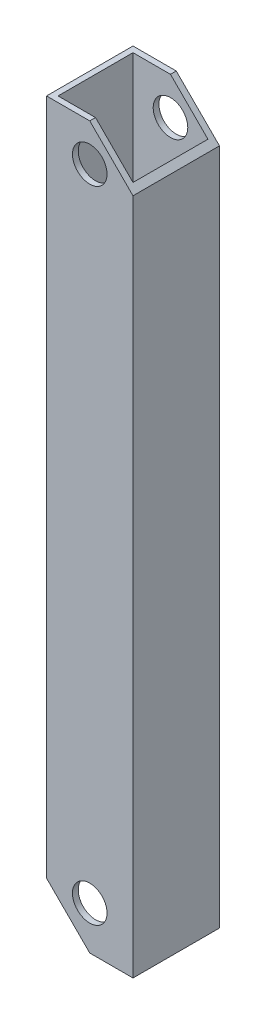
SolidWorks part; units mm, degrees
ref_plane "Front Plane" through (0, 0, 0) normal (0, 0, 1) x (1, 0, 0)
ref_plane "Top Plane" through (0, 0, 0) normal (0, 1, 0) x (1, 0, 0)
ref_plane "Right Plane" through (0, 0, 0) normal (1, 0, 0) x (0, 0, -1)
sketch "Эскиз1" plane through (0, 0, 0) normal (0, 1, 0) x (1, 0, 0)
  line L1 (0, 0) -> (30, 0)
  line L2 (0, 0) -> (0, 30)
  line L3 (0, 30) -> (30, 30)
  line L4 (30, 0) -> (30, 30)
  dimension "D1" = 30
  dimension "D2" = 30
extrude "Бобышка-Вытянуть1" add sketch "Эскиз1" along normal blind 250
sketch "Эскиз2" plane through (0, 250, 0) normal (0, 1, 0) x (1, 0, 0)
  line L0 (0, 30) -> (0, 0) construction
  line L1 (2, 2) -> (28, 2)
  line L2 (2, 2) -> (2, 28)
  line L3 (2, 28) -> (28, 28)
  line L4 (28, 2) -> (28, 28)
  line L5 (30, 30) -> (0, 30) construction
  dimension "D1" = 2
  dimension "D2" = 2
  dimension "D3" = 26
  dimension "D4" = 26
extrude "Вырез-Вытянуть1" cut sketch "Эскиз2" against normal through all
sketch "Эскиз3" plane through (0, 0, 0) normal (0, 0, 1) x (1, 0, 0)
  line L0 (0, 250) -> (0, 0) construction
  line L1 (0, 0) -> (30, 0) construction
  circle A0 centre (15, 15) radius 6
  point P4 (0, 0)
  dimension "D1" = 15
  dimension "D2" = 13
extrude "Вырез-Вытянуть2" cut sketch "Эскиз3" against normal through all
sketch "Эскиз6" plane through (0, 0, 0) normal (0, 0, 1) x (1, 0, 0)
  line L0 (0, 250) -> (30, 250) construction
  line L1 (30, 250) -> (30, 0) construction
  circle A0 centre (15, 237) radius 6
  dimension "D1" = 13
  dimension "D2" = 15
extrude "Вырез-Вытянуть4" cut sketch "Эскиз6" against normal through all
sketch "Эскиз8" plane through (0, 0, 0) normal (0, 0, 1) x (1, 0, 0)
  line L0 (15, 250) -> (30, 235)
  line L1 (0, 250) -> (30, 250) construction
  line L2 (30, 250) -> (30, 0) construction
  line L3 (30, 235) -> (30, 250)
  line L4 (30, 250) -> (15, 250)
  dimension "D1" = 15
extrude "Вырез-Вытянуть5" cut sketch "Эскиз8" against normal through all
sketch "Эскиз9" plane through (0, 0, 0) normal (0, 0, 1) x (1, 0, 0)
  line L0 (15, 0) -> (0, 15)
  line L1 (0, 0) -> (30, 0) construction
  line L2 (0, 250) -> (0, 0) construction
  line L3 (0, 15) -> (0, 0)
  line L4 (0, 0) -> (15, 0)
  dimension "D1" = 15
extrude "Вырез-Вытянуть6" cut sketch "Эскиз9" against normal through all
